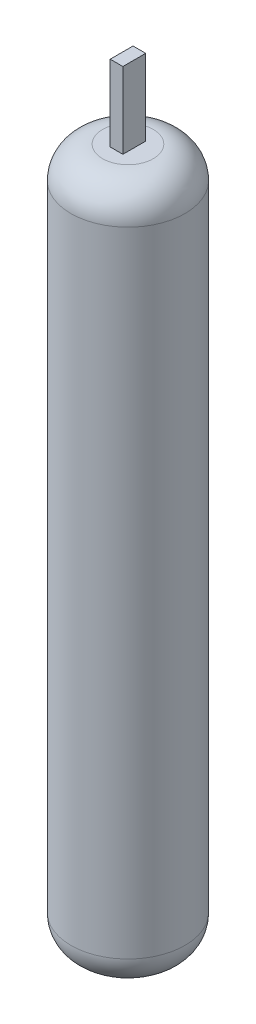
SolidWorks part; units mm, degrees
ref_plane "Front Plane" through (0, 0, 0) normal (0, 0, 1) x (1, 0, 0)
ref_plane "Top Plane" through (0, 0, 0) normal (0, 1, 0) x (1, 0, 0)
ref_plane "Right Plane" through (0, 0, 0) normal (1, 0, 0) x (0, 0, -1)
sketch "Sketch1" plane through (0, 0, 0) normal (0, 1, 0) x (1, 0, 0)
  circle A0 centre (0, 0) radius 4.5
  dimension "D1" = 9
extrude "Boss-Extrude1" add sketch "Sketch1" along normal blind 55 contours A0
sketch "Sketch2" plane through (0, 55, 0) normal (0, 1, 0) x (1, 0, 0)
  line L1 (-0.5, 0.9) -> (0.5, 0.9)
  line L2 (-0.5, 0.9) -> (-0.5, -0.9)
  line L3 (-0.5, -0.9) -> (0.5, -0.9)
  line L4 (0.5, 0.9) -> (0.5, -0.9)
  dimension "D1" = 1.8
  dimension "D2" = 1
  dimension "D3" = 0.5
  dimension "D4" = 0.9
extrude "Boss-Extrude2" add sketch "Sketch2" along normal blind 6
sketch "Sketch3" plane through (0, 0, 0) normal (0, -1, 0) x (1, 0, 0)
  line L0 (-0.6, -1) -> (0.6, -1)
  line L1 (0.6, -1) -> (0.6, 1)
  line L2 (0.6, 1) -> (-0.6, 1)
  line L3 (-0.6, 1) -> (-0.6, -1)
  line L4 (-0.5, -0.9) -> (0.5, -0.9)
  line L5 (0.5, -0.9) -> (0.5, 0.9)
  line L6 (0.5, 0.9) -> (-0.5, 0.9)
  line L7 (-0.5, 0.9) -> (-0.5, -0.9)
  line L8 (-0.5, -0.9) -> (0.5, -0.9) construction
  line L9 (0.5, -0.9) -> (0.5, 0.9) construction
  line L10 (0.5, 0.9) -> (-0.5, 0.9) construction
  line L11 (-0.5, 0.9) -> (-0.5, -0.9) construction
  dimension "D1" = 0
  dimension "D2" = 0.1
extrude "Cut-Extrude1" cut sketch "Sketch3" against normal blind 6
fillet "Fillet1" radius 2.5 2 edges at (0, 0, 4.5) (0, 55, 4.5)
sketch "Sketch4" plane through (0, 0, 0) normal (0, 0, 1) x (1, 0, 0)
  line L0 (0, 0) -> (0, 7.6805) construction
  line L1 (-10, 0) -> (-32, 0)
  line L2 (-10, 0) -> (-10, 1)
  line L3 (-10, 1) -> (-32, 1)
  line L4 (-32, 0) -> (-32, 1)
  line L5 (32, 0) -> (32, 1)
  line L6 (10, 1) -> (32, 1)
  line L7 (10, 0) -> (10, 1)
  line L8 (10, 0) -> (32, 0)
  dimension "D1" = 10
  dimension "D2" = 22
  dimension "D3" = 1
extrude "Boss-Extrude3" [suppressed] add sketch "Sketch4" along normal mid plane 15 separate body
sketch "Sketch5" [suppressed] plane through (0, 0, 0) normal (0, 0, 1) x (1, 0, 0)
  line L0 (21, 1) -> (4.5, 20.6639)
  line L1 (32, 1) -> (10, 1) construction
  line L2 (4.5, 2.5) -> (4.5, 52.5) construction
  line L3 (-4.5, 20.6639) -> (-21, 1)
  line L4 (-4.5, 52.5) -> (-4.5, 2.5) construction
  line L5 (-10, 1) -> (-32, 1) construction
  line L6 (21, 1) -> (18, 1)
  line L7 (18, 1) -> (5.9037, 15.4158)
  line L8 (4.5, 19.2725) -> (4.5, 20.6639)
  line L9 (-4.5, 20.6639) -> (-4.5, 19.2725)
  line L10 (-5.9037, 15.4158) -> (-18, 1)
  line L11 (-18, 1) -> (-21, 1)
  arc A0 (-5.9037, 15.4158) -> (-4.5, 19.2725) centre (-10.5, 19.2725) ccw
  arc A1 (5.9037, 15.4158) -> (4.5, 19.2725) centre (10.5, 19.2725) cw
  point P19 (0, 0)
  point P23 (4.5, 17.0887)
  dimension "D6" = 6
  dimension "D1" = 50
  dimension "D2" = 50
  dimension "D3" = 21
  dimension "D4" = 18
  dimension "D5" = 18
extrude "Boss-Extrude4" [suppressed] add sketch "Sketch5" along normal mid plane 4
sketch "Sketch6" [suppressed] plane through (4.5, 0, 0) normal (-1, 0, 0) x (0, 0, 1)
  line L4 (-2, 20.6639) -> (-2, 19.2725)
  line L5 (-2, 19.2725) -> (2, 19.2725)
  line L6 (2, 19.2725) -> (2, 20.6639)
  line L7 (2, 20.6639) -> (-2, 20.6639)
  line L8 (-2, 20.6639) -> (-2, 19.2725)
  line L9 (-2, 19.2725) -> (2, 19.2725)
  line L10 (2, 19.2725) -> (2, 20.6639)
  line L11 (2, 20.6639) -> (-2, 20.6639)
  dimension "D1" = 0
extrude "Boss-Extrude5" [suppressed] add sketch "Sketch6" along normal up to surface (9 mm away)
